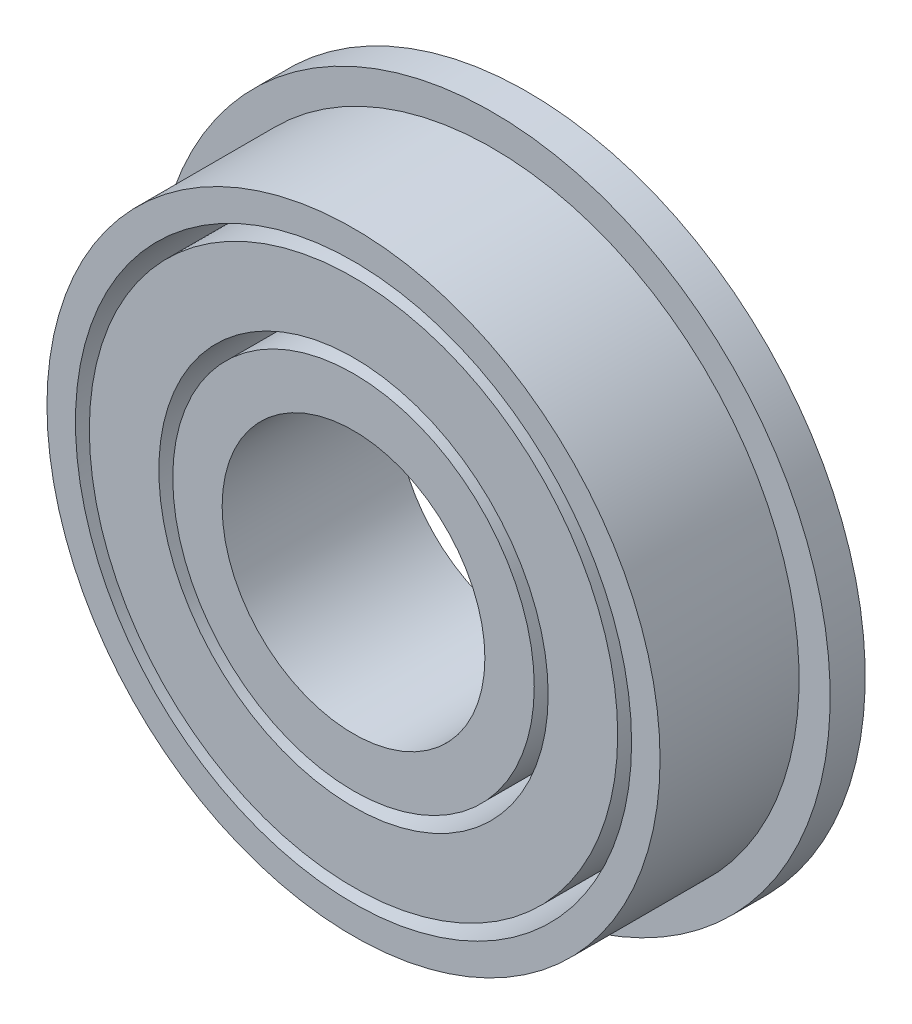
SolidWorks part; units mm, degrees
material "AISI 304"
ref_plane "Alzado" through (0, 0, 0) normal (0, 0, 1) x (1, 0, 0)
ref_plane "Planta" through (0, 0, 0) normal (0, 1, 0) x (1, 0, 0)
ref_plane "Vista lateral" through (0, 0, 0) normal (1, 0, 0) x (0, 0, -1)
sketch "Croquis1" plane through (0, 0, 0) normal (0, 0, 1) x (1, 0, 0)
  circle A0 centre (0, 0) radius 6
  circle A1 centre (0, 0) radius 14
  dimension "D2" = 28
  dimension "D1" = 12
extrude "Saliente-Extruir1" add sketch "Croquis1" along normal blind 7.9502
sketch "Croquis2" plane through (0, 0, 0) normal (0, 0, -1) x (-1, 0, 0)
  circle A0 centre (0, 0) radius 15.42
  circle A1 centre (0, 0) radius 14
  dimension "D1" = 30.84
  dimension "D2" = 28
extrude "Saliente-Extruir2" add sketch "Croquis2" against normal blind 1.6002
sketch "Croquis3" plane through (0, 0, 7.9502) normal (0, 0, 1) x (1, 0, 0)
  circle A0 centre (0, 0) radius 8.255
  circle A1 centre (0, 0) radius 8.89
  circle A2 centre (0, 0) radius 12.7
  circle A3 centre (0, 0) radius 12.065
  dimension "D1" = 25.4
  dimension "D2" = 24.13
  dimension "D3" = 17.78
  dimension "D4" = 16.51
extrude "Cortar-Extruir1" cut sketch "Croquis3" against normal blind 25.4 contours A2 A3 | A1 A0
